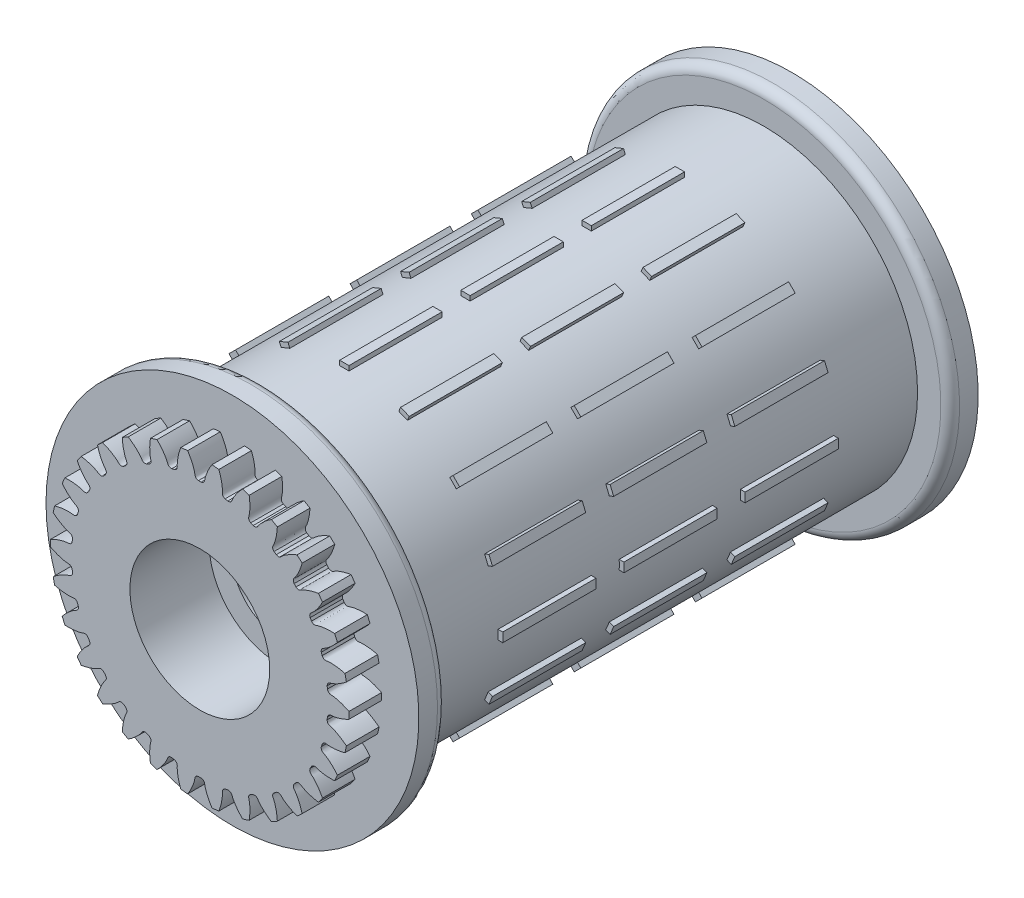
SolidWorks part; units mm, degrees
material "ABS"
ref_plane "前视基准面" through (0, 0, 0) normal (0, 0, 1) x (1, 0, 0)
ref_plane "上视基准面" through (0, 0, 0) normal (0, 1, 0) x (1, 0, 0)
ref_plane "右视基准面" through (0, 0, 0) normal (1, 0, 0) x (0, 0, -1)
other "Configuration Table"
sketch "草图1" plane through (0, 0, 0) normal (0, 1, 0) x (1, 0, 0)
  line L0 (0, 0) -> (0, -60) construction
  line L1 (0, -60) -> (20, -60)
  line L2 (20, -60) -> (20, -57)
  line L3 (20, -57) -> (16.5, -57)
  line L4 (16.5, -57) -> (16.5, -3)
  line L5 (16.5, -3) -> (20, -3)
  line L6 (20, -3) -> (20, 0)
  line L7 (20, 0) -> (0, 0)
  line L8 (7.5, 0) -> (7.5, -5)
  line L9 (7.5, -5) -> (5, -5)
  line L10 (5, -5) -> (5, -55)
  line L11 (5, -55) -> (7.5, -55)
  line L12 (7.5, -55) -> (7.5, -60)
  dimension "D1" = 60
  dimension "D2" = 3
  dimension "D3" = 3
  dimension "D4" = 20
  dimension "D5" = 16.5
  dimension "D6" = 15
  dimension "D7" = 10
  dimension "D8" = 5
  dimension "D9" = 5
  dimension "D10" = 15
revolve "旋转1" add sketch "草图1" angle 360 about L0
fillet "圆角2" radius 1 2 edges at (-20, 0, 57) (-20, 0, 3)
sketch "草图2" plane through (0, 0, 60) normal (0, 0, 1) x (1, 0, 0)
  arc A0 (-2.7162, 13.479) -> (-3.001, 13.4185) centre (0, 0) ccw
  arc A1 (-4.5927, 15.3267) -> (-5.2932, 15.0991) centre (0, 0) ccw
  arc A2 (-5.4593, 12.6198) -> (-5.7253, 12.5013) centre (0, 0) ccw
  arc A3 (-7.6789, 14.0369) -> (-8.3168, 13.6686) centre (0, 0) ccw
  arc A4 (-7.9638, 11.2089) -> (-8.1994, 11.0378) centre (0, 0) ccw
  arc A5 (-10.4296, 12.1336) -> (-10.9769, 11.6407) centre (0, 0) ccw
  arc A6 (-10.1203, 9.3082) -> (-10.3151, 9.0919) centre (0, 0) ccw
  arc A7 (-12.7244, 9.7) -> (-13.1573, 9.1041) centre (0, 0) ccw
  arc A8 (-11.8344, 7.0007) -> (-11.98, 6.7486) centre (0, 0) ccw
  arc A9 (-14.4631, 6.8425) -> (-14.7626, 6.1696) centre (0, 0) ccw
  arc A10 (-13.0313, 4.3872) -> (-13.1213, 4.1103) centre (0, 0) ccw
  arc A11 (-15.5696, 3.6859) -> (-15.7228, 2.9655) centre (0, 0) ccw
  arc A12 (-13.6587, 1.5819) -> (-13.6891, 1.2924) centre (0, 0) ccw
  arc A13 (-15.9958, 0.3683) -> (-15.9958, -0.3683) centre (0, 0) ccw
  arc A14 (-13.6891, -1.2924) -> (-13.6587, -1.5819) centre (0, 0) ccw
  arc A15 (-15.7228, -2.9655) -> (-15.5696, -3.6859) centre (0, 0) ccw
  arc A16 (-13.1213, -4.1103) -> (-13.0313, -4.3872) centre (0, 0) ccw
  arc A17 (-14.7626, -6.1696) -> (-14.4631, -6.8425) centre (0, 0) ccw
  arc A18 (-11.98, -6.7486) -> (-11.8344, -7.0007) centre (0, 0) ccw
  arc A19 (-13.1573, -9.1041) -> (-12.7244, -9.7) centre (0, 0) ccw
  arc A20 (-10.3151, -9.0919) -> (-10.1203, -9.3082) centre (0, 0) ccw
  arc A21 (-10.9769, -11.6407) -> (-10.4296, -12.1336) centre (0, 0) ccw
  arc A22 (-8.1994, -11.0378) -> (-7.9638, -11.2089) centre (0, 0) ccw
  arc A23 (-8.3168, -13.6686) -> (-7.6789, -14.0369) centre (0, 0) ccw
  arc A24 (-5.7253, -12.5013) -> (-5.4593, -12.6198) centre (0, 0) ccw
  arc A25 (-5.2932, -15.0991) -> (-4.5927, -15.3267) centre (0, 0) ccw
  arc A26 (-3.001, -13.4185) -> (-2.7162, -13.479) centre (0, 0) ccw
  arc A27 (-2.0383, -15.8696) -> (-1.3057, -15.9466) centre (0, 0) ccw
  arc A28 (-0.1456, -13.7492) -> (0.1456, -13.7492) centre (0, 0) ccw
  arc A29 (1.3057, -15.9466) -> (2.0383, -15.8696) centre (0, 0) ccw
  arc A30 (2.7162, -13.479) -> (3.001, -13.4185) centre (0, 0) ccw
  arc A31 (4.5927, -15.3267) -> (5.2932, -15.0991) centre (0, 0) ccw
  arc A32 (5.4593, -12.6198) -> (5.7253, -12.5013) centre (0, 0) ccw
  arc A33 (7.6789, -14.0369) -> (8.3168, -13.6686) centre (0, 0) ccw
  arc A34 (7.9638, -11.2089) -> (8.1994, -11.0378) centre (0, 0) ccw
  arc A35 (10.4296, -12.1336) -> (10.9769, -11.6407) centre (0, 0) ccw
  arc A36 (10.1203, -9.3082) -> (10.3151, -9.0919) centre (0, 0) ccw
  arc A37 (12.7244, -9.7) -> (13.1573, -9.1041) centre (0, 0) ccw
  arc A38 (11.8344, -7.0007) -> (11.98, -6.7486) centre (0, 0) ccw
  arc A39 (14.4631, -6.8425) -> (14.7626, -6.1696) centre (0, 0) ccw
  arc A40 (13.0313, -4.3872) -> (13.1213, -4.1103) centre (0, 0) ccw
  arc A41 (15.5696, -3.6859) -> (15.7228, -2.9655) centre (0, 0) ccw
  arc A42 (13.6587, -1.5819) -> (13.6891, -1.2924) centre (0, 0) ccw
  arc A43 (15.9958, -0.3683) -> (15.9958, 0.3683) centre (0, 0) ccw
  arc A44 (13.6891, 1.2924) -> (13.6587, 1.5819) centre (0, 0) ccw
  arc A45 (15.7228, 2.9655) -> (15.5696, 3.6859) centre (0, 0) ccw
  arc A46 (13.1213, 4.1103) -> (13.0313, 4.3872) centre (0, 0) ccw
  arc A47 (14.7626, 6.1696) -> (14.4631, 6.8425) centre (0, 0) ccw
  arc A48 (11.98, 6.7486) -> (11.8344, 7.0007) centre (0, 0) ccw
  arc A49 (13.1573, 9.1041) -> (12.7244, 9.7) centre (0, 0) ccw
  arc A50 (10.3151, 9.0919) -> (10.1203, 9.3082) centre (0, 0) ccw
  arc A51 (10.9769, 11.6407) -> (10.4296, 12.1336) centre (0, 0) ccw
  arc A52 (8.1994, 11.0378) -> (7.9638, 11.2089) centre (0, 0) ccw
  arc A53 (8.3168, 13.6686) -> (7.6789, 14.0369) centre (0, 0) ccw
  arc A54 (5.7253, 12.5013) -> (5.4593, 12.6198) centre (0, 0) ccw
  arc A55 (5.2932, 15.0991) -> (4.5927, 15.3267) centre (0, 0) ccw
  arc A56 (3.001, 13.4185) -> (2.7162, 13.479) centre (0, 0) ccw
  arc A57 (2.0383, 15.8696) -> (1.3057, 15.9466) centre (0, 0) ccw
  arc A58 (0.1456, 13.7492) -> (-0.1456, 13.7492) centre (0, 0) ccw
  arc A59 (-1.3057, 15.9466) -> (-2.0383, 15.8696) centre (0, 0) ccw
  circle A60 centre (0, 0) radius 7.5
  spline S0 degree 3 poles (-3.001, 13.4185) (-3.369, 13.4055) (-3.4197, 13.6341) (-3.5175, 13.8601) (-3.5386, 13.9063) (-3.5727, 13.9775) (-3.6247, 14.0776) (-3.7001, 14.2098) (-3.7927, 14.3581) (-3.9038, 14.5213) (-4.0348, 14.6979) (-4.1869, 14.8868) (-4.3612, 15.0865) (-4.5001, 15.2333) (-4.5801, 15.314) (-4.5927, 15.3267) knots 0.548501 0.548501 0.548501 0.548501 0.663825 0.671913 0.681013 0.691124 0.714378 0.741677 0.77302 0.808408 0.847839 0.891315 0.938834 0.990398 1 1 1 1
  spline S1 degree 3 poles (-5.2932, 15.0991) (-5.3109, 14.9867) (-5.3377, 14.7864) (-5.363, 14.5047) (-5.375, 14.2625) (-5.3771, 14.0426) (-5.372, 13.8735) (-5.3628, 13.7234) (-5.353, 13.6148) (-5.3383, 13.4935) (-5.3254, 13.408) (-5.3112, 13.3304) (-5.301, 13.2806) (-5.2473, 13.0403) (-5.154, 12.8255) (-5.4593, 12.6198) knots 0 0 0 0 0.061166 0.108685 0.152161 0.191592 0.22698 0.243157 0.272478 0.285622 0.308876 0.318987 0.328087 0.336175 0.451499 0.451499 0.451499 0.451499
  spline S2 degree 3 poles (-5.7253, 12.5013) (-6.0825, 12.4121) (-6.1797, 12.6251) (-6.3223, 12.8259) (-6.3525, 12.8667) (-6.4007, 12.9292) (-6.4724, 13.0163) (-6.5736, 13.13) (-6.6951, 13.2558) (-6.8377, 13.3923) (-7.0025, 13.5379) (-7.1905, 13.691) (-7.4026, 13.85) (-7.5689, 13.9647) (-7.664, 14.0271) (-7.6789, 14.0369) knots 0.548501 0.548501 0.548501 0.548501 0.663825 0.671913 0.681013 0.691124 0.714378 0.741677 0.77302 0.808408 0.847839 0.891315 0.938834 0.990398 1 1 1 1
  spline S3 degree 3 poles (-8.3168, 13.6686) (-8.3107, 13.5551) (-8.2953, 13.3536) (-8.2615, 13.0727) (-8.2229, 12.8333) (-8.1792, 12.6177) (-8.139, 12.4534) (-8.0989, 12.3085) (-8.0667, 12.2043) (-8.0271, 12.0888) (-7.9967, 12.0078) (-7.9666, 11.9348) (-7.9464, 11.8883) (-7.8439, 11.6643) (-7.7079, 11.4737) (-7.9638, 11.2089) knots 0 0 0 0 0.061166 0.108685 0.152161 0.191592 0.22698 0.243157 0.272478 0.285622 0.308876 0.318987 0.328087 0.336175 0.451499 0.451499 0.451499 0.451499
  spline S4 degree 3 poles (-8.1994, 11.0378) (-8.5302, 10.8762) (-8.6695, 11.0644) (-8.8508, 11.2311) (-8.8888, 11.2648) (-8.949, 11.3159) (-9.0372, 11.3862) (-9.1599, 11.4764) (-9.3048, 11.5742) (-9.4727, 11.678) (-9.6642, 11.7861) (-9.8799, 11.8968) (-10.1204, 12.0083) (-10.307, 12.0859) (-10.4129, 12.1272) (-10.4296, 12.1336) knots 0.548501 0.548501 0.548501 0.548501 0.663825 0.671913 0.681013 0.691124 0.714378 0.741677 0.77302 0.808408 0.847839 0.891315 0.938834 0.990398 1 1 1 1
  spline S5 degree 3 poles (-10.9769, 11.6407) (-10.9474, 11.531) (-10.8904, 11.3371) (-10.7989, 11.0694) (-10.7114, 10.8432) (-10.6239, 10.6414) (-10.5504, 10.489) (-10.481, 10.3557) (-10.4278, 10.2605) (-10.365, 10.1557) (-10.3185, 10.0828) (-10.2739, 10.0176) (-10.2444, 9.9763) (-10.0976, 9.7786) (-9.925, 9.6204) (-10.1203, 9.3082) knots 0 0 0 0 0.061166 0.108685 0.152161 0.191592 0.22698 0.243157 0.272478 0.285622 0.308876 0.318987 0.328087 0.336175 0.451499 0.451499 0.451499 0.451499
  spline S6 degree 3 poles (-10.3151, 9.0919) (-10.6051, 8.865) (-10.7805, 9.0201) (-10.9925, 9.1455) (-11.0367, 9.1705) (-11.1061, 9.208) (-11.207, 9.2585) (-11.3458, 9.3211) (-11.5079, 9.3867) (-11.6936, 9.4533) (-11.9035, 9.5193) (-12.1375, 9.5827) (-12.3959, 9.6417) (-12.5945, 9.6789) (-12.7067, 9.6972) (-12.7244, 9.7) knots 0.548501 0.548501 0.548501 0.548501 0.663825 0.671913 0.681013 0.691124 0.714378 0.741677 0.77302 0.808408 0.847839 0.891315 0.938834 0.990398 1 1 1 1
  spline S7 degree 3 poles (-13.1573, 9.1041) (-13.1056, 9.0029) (-13.0096, 8.8251) (-12.8644, 8.5823) (-12.7317, 8.3793) (-12.6042, 8.2001) (-12.5006, 8.0663) (-12.405, 7.9503) (-12.3332, 7.8682) (-12.25, 7.7787) (-12.1893, 7.7171) (-12.1322, 7.6627) (-12.0948, 7.6284) (-11.91, 7.4655) (-11.7083, 7.3466) (-11.8344, 7.0007) knots 0 0 0 0 0.061166 0.108685 0.152161 0.191592 0.22698 0.243157 0.272478 0.285622 0.308876 0.318987 0.328087 0.336175 0.451499 0.451499 0.451499 0.451499
  spline S8 degree 3 poles (-11.98, 6.7486) (-12.2165, 6.4663) (-12.4203, 6.5816) (-12.6538, 6.6602) (-12.7022, 6.6755) (-12.7779, 6.6977) (-12.8871, 6.7261) (-13.0358, 6.7585) (-13.208, 6.7889) (-13.4036, 6.8155) (-13.6225, 6.8364) (-13.8646, 6.8498) (-14.1297, 6.8538) (-14.3317, 6.8488) (-14.4452, 6.8434) (-14.4631, 6.8425) knots 0.548501 0.548501 0.548501 0.548501 0.663825 0.671913 0.681013 0.691124 0.714378 0.741677 0.77302 0.808408 0.847839 0.891315 0.938834 0.990398 1 1 1 1
  spline S9 degree 3 poles (-14.7626, 6.1696) (-14.691, 6.0814) (-14.5601, 5.9274) (-14.3676, 5.7201) (-14.1957, 5.5491) (-14.0336, 5.4003) (-13.9045, 5.291) (-13.7869, 5.1974) (-13.6996, 5.132) (-13.5996, 5.0618) (-13.5275, 5.0142) (-13.4602, 4.9728) (-13.4165, 4.947) (-13.2019, 4.8261) (-12.9799, 4.7518) (-13.0313, 4.3872) knots 0 0 0 0 0.061166 0.108685 0.152161 0.191592 0.22698 0.243157 0.272478 0.285622 0.308876 0.318987 0.328087 0.336175 0.451499 0.451499 0.451499 0.451499
  spline S10 degree 3 poles (-13.1213, 4.1103) (-13.294, 3.7851) (-13.5173, 3.8555) (-13.762, 3.8838) (-13.8125, 3.8887) (-13.8912, 3.8947) (-14.0039, 3.8997) (-14.1561, 3.9005) (-14.3309, 3.8945) (-14.5277, 3.8798) (-14.7462, 3.8547) (-14.9858, 3.8174) (-15.2459, 3.7663) (-15.4424, 3.7194) (-15.5524, 3.6905) (-15.5696, 3.6859) knots 0.548501 0.548501 0.548501 0.548501 0.663825 0.671913 0.681013 0.691124 0.714378 0.741677 0.77302 0.808408 0.847839 0.891315 0.938834 0.990398 1 1 1 1
  spline S11 degree 3 poles (-15.7228, 2.9655) (-15.6343, 2.894) (-15.4743, 2.7706) (-15.2429, 2.6079) (-15.0392, 2.4764) (-14.8498, 2.3646) (-14.7008, 2.2845) (-14.5662, 2.2174) (-14.4673, 2.1716) (-14.3549, 2.1237) (-14.2744, 2.0921) (-14.2, 2.0656) (-14.1519, 2.0495) (-13.9168, 1.9758) (-13.6842, 1.9493) (-13.6587, 1.5819) knots 0 0 0 0 0.061166 0.108685 0.152161 0.191592 0.22698 0.243157 0.272478 0.285622 0.308876 0.318987 0.328087 0.336175 0.451499 0.451499 0.451499 0.451499
  spline S12 degree 3 poles (-13.6891, 1.2924) (-13.7904, 0.9384) (-14.0235, 0.9608) (-14.2687, 0.9376) (-14.3192, 0.9319) (-14.3974, 0.9214) (-14.5087, 0.903) (-14.6578, 0.8721) (-14.8274, 0.8298) (-15.0169, 0.7745) (-15.2254, 0.7046) (-15.452, 0.6183) (-15.6958, 0.5142) (-15.8783, 0.4275) (-15.9798, 0.3764) (-15.9958, 0.3683) knots 0.548501 0.548501 0.548501 0.548501 0.663825 0.671913 0.681013 0.691124 0.714378 0.741677 0.77302 0.808408 0.847839 0.891315 0.938834 0.990398 1 1 1 1
  spline S13 degree 3 poles (-15.9958, -0.3683) (-15.8944, -0.4198) (-15.7122, -0.5072) (-15.452, -0.6183) (-15.2254, -0.7046) (-15.0169, -0.7745) (-14.8545, -0.8219) (-14.7089, -0.8596) (-14.6026, -0.8838) (-14.4827, -0.9073) (-14.3974, -0.9214) (-14.3192, -0.9319) (-14.2687, -0.9376) (-14.0235, -0.9608) (-13.7904, -0.9384) (-13.6891, -1.2924) knots 0 0 0 0 0.061166 0.108685 0.152161 0.191592 0.22698 0.243157 0.272478 0.285622 0.308876 0.318987 0.328087 0.336175 0.451499 0.451499 0.451499 0.451499
  spline S14 degree 3 poles (-13.6587, -1.5819) (-13.6842, -1.9493) (-13.9168, -1.9758) (-14.1519, -2.0495) (-14.2, -2.0656) (-14.2744, -2.0921) (-14.3794, -2.1333) (-14.5188, -2.1945) (-14.6759, -2.2711) (-14.8498, -2.3646) (-15.0392, -2.4764) (-15.2429, -2.6079) (-15.4597, -2.7604) (-15.6202, -2.8831) (-15.7089, -2.9543) (-15.7228, -2.9655) knots 0.548501 0.548501 0.548501 0.548501 0.663825 0.671913 0.681013 0.691124 0.714378 0.741677 0.77302 0.808408 0.847839 0.891315 0.938834 0.990398 1 1 1 1
  spline S15 degree 3 poles (-15.5696, -3.6859) (-15.4598, -3.7152) (-15.2634, -3.7629) (-14.9858, -3.8174) (-14.7462, -3.8547) (-14.5277, -3.8798) (-14.359, -3.8924) (-14.2088, -3.8989) (-14.0997, -3.9005) (-13.9776, -3.8986) (-13.8912, -3.8947) (-13.8125, -3.8887) (-13.762, -3.8838) (-13.5173, -3.8555) (-13.294, -3.7851) (-13.1213, -4.1103) knots 0 0 0 0 0.061166 0.108685 0.152161 0.191592 0.22698 0.243157 0.272478 0.285622 0.308876 0.318987 0.328087 0.336175 0.451499 0.451499 0.451499 0.451499
  spline S16 degree 3 poles (-13.0313, -4.3872) (-12.9799, -4.7518) (-13.2019, -4.8261) (-13.4165, -4.947) (-13.4602, -4.9728) (-13.5275, -5.0142) (-13.6216, -5.0763) (-13.7452, -5.1652) (-13.883, -5.2728) (-14.0336, -5.4003) (-14.1957, -5.5491) (-14.3676, -5.7201) (-14.5479, -5.9143) (-14.6794, -6.0678) (-14.7514, -6.1558) (-14.7626, -6.1696) knots 0.548501 0.548501 0.548501 0.548501 0.663825 0.671913 0.681013 0.691124 0.714378 0.741677 0.77302 0.808408 0.847839 0.891315 0.938834 0.990398 1 1 1 1
  spline S17 degree 3 poles (-14.4631, -6.8425) (-14.3495, -6.8483) (-14.1475, -6.8541) (-13.8646, -6.8498) (-13.6225, -6.8364) (-13.4036, -6.8155) (-13.2359, -6.7927) (-13.0876, -6.7679) (-12.9807, -6.7468) (-12.8616, -6.7195) (-12.7779, -6.6977) (-12.7022, -6.6755) (-12.6538, -6.6602) (-12.4203, -6.5816) (-12.2165, -6.4663) (-11.98, -6.7486) knots 0 0 0 0 0.061166 0.108685 0.152161 0.191592 0.22698 0.243157 0.272478 0.285622 0.308876 0.318987 0.328087 0.336175 0.451499 0.451499 0.451499 0.451499
  spline S18 degree 3 poles (-11.8344, -7.0007) (-11.7083, -7.3466) (-11.91, -7.4655) (-12.0948, -7.6284) (-12.1322, -7.6627) (-12.1893, -7.7171) (-12.2685, -7.7975) (-12.371, -7.9101) (-12.4834, -8.044) (-12.6042, -8.2001) (-12.7317, -8.3793) (-12.8644, -8.5823) (-13.0004, -8.8097) (-13.0971, -8.9872) (-13.1492, -9.0882) (-13.1573, -9.1041) knots 0.548501 0.548501 0.548501 0.548501 0.663825 0.671913 0.681013 0.691124 0.714378 0.741677 0.77302 0.808408 0.847839 0.891315 0.938834 0.990398 1 1 1 1
  spline S19 degree 3 poles (-12.7244, -9.7) (-12.6121, -9.6821) (-12.4133, -9.6457) (-12.1375, -9.5827) (-11.9035, -9.5193) (-11.6936, -9.4533) (-11.5344, -9.3962) (-11.3945, -9.3411) (-11.2943, -9.2982) (-11.1835, -9.2467) (-11.1061, -9.208) (-11.0367, -9.1705) (-10.9925, -9.1455) (-10.7805, -9.0201) (-10.6051, -8.865) (-10.3151, -9.0919) knots 0 0 0 0 0.061166 0.108685 0.152161 0.191592 0.22698 0.243157 0.272478 0.285622 0.308876 0.318987 0.328087 0.336175 0.451499 0.451499 0.451499 0.451499
  spline S20 degree 3 poles (-10.1203, -9.3082) (-9.925, -9.6204) (-10.0976, -9.7786) (-10.2444, -9.9763) (-10.2739, -10.0176) (-10.3185, -10.0828) (-10.3792, -10.1778) (-10.456, -10.3093) (-10.5382, -10.4636) (-10.6239, -10.6415) (-10.7114, -10.8432) (-10.7989, -11.0694) (-10.8847, -11.3202) (-10.9423, -11.5138) (-10.9723, -11.6235) (-10.9769, -11.6407) knots 0.548501 0.548501 0.548501 0.548501 0.663825 0.671913 0.681013 0.691124 0.714378 0.741677 0.77302 0.808408 0.847839 0.891315 0.938834 0.990398 1 1 1 1
  spline S21 degree 3 poles (-10.4296, -12.1336) (-10.3235, -12.0927) (-10.1366, -12.0158) (-9.8799, -11.8968) (-9.6642, -11.7861) (-9.4727, -11.678) (-9.3288, -11.589) (-9.2034, -11.506) (-9.1142, -11.4432) (-9.0166, -11.3698) (-8.949, -11.3159) (-8.8888, -11.2648) (-8.8508, -11.2311) (-8.6695, -11.0644) (-8.5302, -10.8762) (-8.1994, -11.0378) knots 0 0 0 0 0.061166 0.108685 0.152161 0.191592 0.22698 0.243157 0.272478 0.285622 0.308876 0.318987 0.328087 0.336175 0.451499 0.451499 0.451499 0.451499
  spline S22 degree 3 poles (-7.9638, -11.2089) (-7.7079, -11.4737) (-7.8439, -11.6643) (-7.9464, -11.8883) (-7.9666, -11.9348) (-7.9967, -12.0078) (-8.0363, -12.1134) (-8.0841, -12.258) (-8.1324, -12.426) (-8.1792, -12.6177) (-8.2229, -12.8333) (-8.2615, -13.0727) (-8.2932, -13.3358) (-8.3094, -13.5373) (-8.3159, -13.6508) (-8.3168, -13.6686) knots 0.548501 0.548501 0.548501 0.548501 0.663825 0.671913 0.681013 0.691124 0.714378 0.741677 0.77302 0.808408 0.847839 0.891315 0.938834 0.990398 1 1 1 1
  spline S23 degree 3 poles (-7.6789, -14.0369) (-7.5837, -13.9748) (-7.4169, -13.8608) (-7.1905, -13.691) (-7.0025, -13.5379) (-6.8377, -13.3923) (-6.7154, -13.2753) (-6.61, -13.1681) (-6.5359, -13.0881) (-6.4556, -12.996) (-6.4007, -12.9292) (-6.3525, -12.8667) (-6.3223, -12.8259) (-6.1797, -12.6251) (-6.0825, -12.4121) (-5.7253, -12.5013) knots 0 0 0 0 0.061166 0.108685 0.152161 0.191592 0.22698 0.243157 0.272478 0.285622 0.308876 0.318987 0.328087 0.336175 0.451499 0.451499 0.451499 0.451499
  spline S24 degree 3 poles (-5.4593, -12.6198) (-5.154, -12.8255) (-5.2473, -13.0403) (-5.301, -13.2806) (-5.3112, -13.3304) (-5.3254, -13.408) (-5.3422, -13.5195) (-5.3589, -13.6709) (-5.3711, -13.8453) (-5.3771, -14.0426) (-5.375, -14.2625) (-5.363, -14.5047) (-5.3393, -14.7687) (-5.3132, -14.9691) (-5.296, -15.0814) (-5.2932, -15.0991) knots 0.548501 0.548501 0.548501 0.548501 0.663825 0.671913 0.681013 0.691124 0.714378 0.741677 0.77302 0.808408 0.847839 0.891315 0.938834 0.990398 1 1 1 1
  spline S25 degree 3 poles (-4.5927, -15.3267) (-4.5124, -15.2462) (-4.373, -15.0999) (-4.1869, -14.8868) (-4.0348, -14.6979) (-3.9038, -14.5213) (-3.8086, -14.3814) (-3.7278, -14.2546) (-3.6719, -14.161) (-3.6125, -14.0542) (-3.5727, -13.9775) (-3.5386, -13.9063) (-3.5175, -13.8601) (-3.4197, -13.6341) (-3.369, -13.4055) (-3.001, -13.4185) knots 0 0 0 0 0.061166 0.108685 0.152161 0.191592 0.22698 0.243157 0.272478 0.285622 0.308876 0.318987 0.328087 0.336175 0.451499 0.451499 0.451499 0.451499
  spline S26 degree 3 poles (-2.7162, -13.479) (-2.3748, -13.6168) (-2.4214, -13.8463) (-2.424, -14.0926) (-2.4236, -14.1433) (-2.4213, -14.2222) (-2.4146, -14.3348) (-2.3994, -14.4863) (-2.3752, -14.6594) (-2.34, -14.8537) (-2.2922, -15.0683) (-2.2301, -15.3027) (-2.152, -15.556) (-2.0849, -15.7466) (-2.0447, -15.853) (-2.0383, -15.8696) knots 0.548501 0.548501 0.548501 0.548501 0.663825 0.671913 0.681013 0.691124 0.714378 0.741677 0.77302 0.808408 0.847839 0.891315 0.938834 0.990398 1 1 1 1
  spline S27 degree 3 poles (-1.3057, -15.9466) (-1.2439, -15.8512) (-1.138, -15.6791) (-1.0003, -15.432) (-0.8908, -15.2156) (-0.7994, -15.0156) (-0.7353, -14.859) (-0.6826, -14.7182) (-0.6474, -14.615) (-0.6116, -14.4982) (-0.5886, -14.4148) (-0.57, -14.3381) (-0.559, -14.2886) (-0.5103, -14.0471) (-0.5082, -13.813) (-0.1456, -13.7492) knots 0 0 0 0 0.061166 0.108685 0.152161 0.191592 0.22698 0.243157 0.272478 0.285622 0.308876 0.318987 0.328087 0.336175 0.451499 0.451499 0.451499 0.451499
  spline S28 degree 3 poles (0.1456, -13.7492) (0.5082, -13.813) (0.5103, -14.0471) (0.559, -14.2886) (0.57, -14.3381) (0.5886, -14.4148) (0.6186, -14.5236) (0.6649, -14.6686) (0.7246, -14.8329) (0.7994, -15.0156) (0.8908, -15.2156) (1.0003, -15.432) (1.1293, -15.6635) (1.2346, -15.836) (1.296, -15.9316) (1.3057, -15.9466) knots 0.548501 0.548501 0.548501 0.548501 0.663825 0.671913 0.681013 0.691124 0.714378 0.741677 0.77302 0.808408 0.847839 0.891315 0.938834 0.990398 1 1 1 1
  spline S29 degree 3 poles (2.0383, -15.8696) (2.0789, -15.7634) (2.1468, -15.5731) (2.2301, -15.3027) (2.2922, -15.0683) (2.34, -14.8537) (2.3701, -14.6872) (2.3924, -14.5385) (2.4054, -14.4302) (2.4161, -14.3085) (2.4213, -14.2222) (2.4236, -14.1433) (2.424, -14.0926) (2.4214, -13.8463) (2.3748, -13.6168) (2.7162, -13.479) knots 0 0 0 0 0.061166 0.108685 0.152161 0.191592 0.22698 0.243157 0.272478 0.285622 0.308876 0.318987 0.328087 0.336175 0.451499 0.451499 0.451499 0.451499
  spline S30 degree 3 poles (3.001, -13.4185) (3.369, -13.4055) (3.4197, -13.6341) (3.5175, -13.8601) (3.5386, -13.9063) (3.5727, -13.9775) (3.6247, -14.0776) (3.7001, -14.2098) (3.7927, -14.3581) (3.9038, -14.5213) (4.0348, -14.6979) (4.1869, -14.8868) (4.3612, -15.0865) (4.5001, -15.2333) (4.5801, -15.314) (4.5927, -15.3267) knots 0.548501 0.548501 0.548501 0.548501 0.663825 0.671913 0.681013 0.691124 0.714378 0.741677 0.77302 0.808408 0.847839 0.891315 0.938834 0.990398 1 1 1 1
  spline S31 degree 3 poles (5.2932, -15.0991) (5.3109, -14.9867) (5.3377, -14.7864) (5.363, -14.5047) (5.375, -14.2625) (5.3771, -14.0426) (5.372, -13.8735) (5.3628, -13.7234) (5.353, -13.6148) (5.3383, -13.4935) (5.3254, -13.408) (5.3112, -13.3304) (5.301, -13.2806) (5.2473, -13.0403) (5.154, -12.8255) (5.4593, -12.6198) knots 0 0 0 0 0.061166 0.108685 0.152161 0.191592 0.22698 0.243157 0.272478 0.285622 0.308876 0.318987 0.328087 0.336175 0.451499 0.451499 0.451499 0.451499
  spline S32 degree 3 poles (5.7253, -12.5013) (6.0825, -12.4121) (6.1797, -12.6251) (6.3223, -12.8259) (6.3525, -12.8667) (6.4007, -12.9292) (6.4724, -13.0163) (6.5736, -13.13) (6.6951, -13.2558) (6.8377, -13.3923) (7.0025, -13.5379) (7.1905, -13.691) (7.4026, -13.85) (7.5689, -13.9647) (7.664, -14.0271) (7.6789, -14.0369) knots 0.548501 0.548501 0.548501 0.548501 0.663825 0.671913 0.681013 0.691124 0.714378 0.741677 0.77302 0.808408 0.847839 0.891315 0.938834 0.990398 1 1 1 1
  spline S33 degree 3 poles (8.3168, -13.6686) (8.3107, -13.5551) (8.2953, -13.3536) (8.2615, -13.0727) (8.2229, -12.8333) (8.1792, -12.6177) (8.139, -12.4534) (8.0989, -12.3085) (8.0667, -12.2043) (8.0271, -12.0888) (7.9967, -12.0078) (7.9666, -11.9348) (7.9464, -11.8883) (7.8439, -11.6643) (7.7079, -11.4737) (7.9638, -11.2089) knots 0 0 0 0 0.061166 0.108685 0.152161 0.191592 0.22698 0.243157 0.272478 0.285622 0.308876 0.318987 0.328087 0.336175 0.451499 0.451499 0.451499 0.451499
  spline S34 degree 3 poles (8.1994, -11.0378) (8.5302, -10.8762) (8.6695, -11.0644) (8.8508, -11.2311) (8.8888, -11.2648) (8.949, -11.3159) (9.0372, -11.3862) (9.1599, -11.4764) (9.3048, -11.5742) (9.4727, -11.678) (9.6642, -11.7861) (9.8799, -11.8968) (10.1204, -12.0083) (10.307, -12.0859) (10.4129, -12.1272) (10.4296, -12.1336) knots 0.548501 0.548501 0.548501 0.548501 0.663825 0.671913 0.681013 0.691124 0.714378 0.741677 0.77302 0.808408 0.847839 0.891315 0.938834 0.990398 1 1 1 1
  spline S35 degree 3 poles (10.9769, -11.6407) (10.9474, -11.531) (10.8904, -11.3371) (10.7989, -11.0694) (10.7114, -10.8432) (10.6239, -10.6414) (10.5504, -10.489) (10.481, -10.3557) (10.4278, -10.2605) (10.365, -10.1557) (10.3185, -10.0828) (10.2739, -10.0176) (10.2444, -9.9763) (10.0976, -9.7786) (9.925, -9.6204) (10.1203, -9.3082) knots 0 0 0 0 0.061166 0.108685 0.152161 0.191592 0.22698 0.243157 0.272478 0.285622 0.308876 0.318987 0.328087 0.336175 0.451499 0.451499 0.451499 0.451499
  spline S36 degree 3 poles (10.3151, -9.0919) (10.6051, -8.865) (10.7805, -9.0201) (10.9925, -9.1455) (11.0367, -9.1705) (11.1061, -9.208) (11.207, -9.2585) (11.3458, -9.3211) (11.5079, -9.3867) (11.6936, -9.4533) (11.9035, -9.5193) (12.1375, -9.5827) (12.3959, -9.6417) (12.5945, -9.6789) (12.7067, -9.6972) (12.7244, -9.7) knots 0.548501 0.548501 0.548501 0.548501 0.663825 0.671913 0.681013 0.691124 0.714378 0.741677 0.77302 0.808408 0.847839 0.891315 0.938834 0.990398 1 1 1 1
  spline S37 degree 3 poles (13.1573, -9.1041) (13.1056, -9.0029) (13.0096, -8.8251) (12.8644, -8.5823) (12.7317, -8.3793) (12.6042, -8.2001) (12.5006, -8.0663) (12.405, -7.9503) (12.3332, -7.8682) (12.25, -7.7787) (12.1893, -7.7171) (12.1322, -7.6627) (12.0948, -7.6284) (11.91, -7.4655) (11.7083, -7.3466) (11.8344, -7.0007) knots 0 0 0 0 0.061166 0.108685 0.152161 0.191592 0.22698 0.243157 0.272478 0.285622 0.308876 0.318987 0.328087 0.336175 0.451499 0.451499 0.451499 0.451499
  spline S38 degree 3 poles (11.98, -6.7486) (12.2165, -6.4663) (12.4203, -6.5816) (12.6538, -6.6602) (12.7022, -6.6755) (12.7779, -6.6977) (12.8871, -6.7261) (13.0358, -6.7585) (13.208, -6.7889) (13.4036, -6.8155) (13.6225, -6.8364) (13.8646, -6.8498) (14.1297, -6.8538) (14.3317, -6.8488) (14.4452, -6.8434) (14.4631, -6.8425) knots 0.548501 0.548501 0.548501 0.548501 0.663825 0.671913 0.681013 0.691124 0.714378 0.741677 0.77302 0.808408 0.847839 0.891315 0.938834 0.990398 1 1 1 1
  spline S39 degree 3 poles (14.7626, -6.1696) (14.691, -6.0814) (14.5601, -5.9274) (14.3676, -5.7201) (14.1957, -5.5491) (14.0336, -5.4003) (13.9045, -5.291) (13.7869, -5.1974) (13.6996, -5.132) (13.5996, -5.0618) (13.5275, -5.0142) (13.4602, -4.9728) (13.4165, -4.947) (13.2019, -4.8261) (12.9799, -4.7518) (13.0313, -4.3872) knots 0 0 0 0 0.061166 0.108685 0.152161 0.191592 0.22698 0.243157 0.272478 0.285622 0.308876 0.318987 0.328087 0.336175 0.451499 0.451499 0.451499 0.451499
  spline S40 degree 3 poles (13.1213, -4.1103) (13.294, -3.7851) (13.5173, -3.8555) (13.762, -3.8838) (13.8125, -3.8887) (13.8912, -3.8947) (14.0039, -3.8997) (14.1561, -3.9005) (14.3309, -3.8945) (14.5277, -3.8798) (14.7462, -3.8547) (14.9858, -3.8174) (15.2459, -3.7663) (15.4424, -3.7194) (15.5524, -3.6905) (15.5696, -3.6859) knots 0.548501 0.548501 0.548501 0.548501 0.663825 0.671913 0.681013 0.691124 0.714378 0.741677 0.77302 0.808408 0.847839 0.891315 0.938834 0.990398 1 1 1 1
  spline S41 degree 3 poles (15.7228, -2.9655) (15.6343, -2.894) (15.4743, -2.7706) (15.2429, -2.6079) (15.0392, -2.4764) (14.8498, -2.3646) (14.7008, -2.2845) (14.5662, -2.2174) (14.4673, -2.1716) (14.3549, -2.1237) (14.2744, -2.0921) (14.2, -2.0656) (14.1519, -2.0495) (13.9168, -1.9758) (13.6842, -1.9493) (13.6587, -1.5819) knots 0 0 0 0 0.061166 0.108685 0.152161 0.191592 0.22698 0.243157 0.272478 0.285622 0.308876 0.318987 0.328087 0.336175 0.451499 0.451499 0.451499 0.451499
  spline S42 degree 3 poles (13.6891, -1.2924) (13.7904, -0.9384) (14.0235, -0.9608) (14.2687, -0.9376) (14.3192, -0.9319) (14.3974, -0.9214) (14.5087, -0.903) (14.6578, -0.8721) (14.8274, -0.8298) (15.0169, -0.7745) (15.2254, -0.7046) (15.452, -0.6183) (15.6958, -0.5142) (15.8783, -0.4275) (15.9798, -0.3764) (15.9958, -0.3683) knots 0.548501 0.548501 0.548501 0.548501 0.663825 0.671913 0.681013 0.691124 0.714378 0.741677 0.77302 0.808408 0.847839 0.891315 0.938834 0.990398 1 1 1 1
  spline S43 degree 3 poles (15.9958, 0.3683) (15.8944, 0.4198) (15.7122, 0.5072) (15.452, 0.6183) (15.2254, 0.7046) (15.0169, 0.7745) (14.8545, 0.8219) (14.7089, 0.8596) (14.6026, 0.8838) (14.4827, 0.9073) (14.3974, 0.9214) (14.3192, 0.9319) (14.2687, 0.9376) (14.0235, 0.9608) (13.7904, 0.9384) (13.6891, 1.2924) knots 0 0 0 0 0.061166 0.108685 0.152161 0.191592 0.22698 0.243157 0.272478 0.285622 0.308876 0.318987 0.328087 0.336175 0.451499 0.451499 0.451499 0.451499
  spline S44 degree 3 poles (13.6587, 1.5819) (13.6842, 1.9493) (13.9168, 1.9758) (14.1519, 2.0495) (14.2, 2.0656) (14.2744, 2.0921) (14.3794, 2.1333) (14.5188, 2.1945) (14.6759, 2.2711) (14.8498, 2.3646) (15.0392, 2.4764) (15.2429, 2.6079) (15.4597, 2.7604) (15.6202, 2.8831) (15.7089, 2.9543) (15.7228, 2.9655) knots 0.548501 0.548501 0.548501 0.548501 0.663825 0.671913 0.681013 0.691124 0.714378 0.741677 0.77302 0.808408 0.847839 0.891315 0.938834 0.990398 1 1 1 1
  spline S45 degree 3 poles (15.5696, 3.6859) (15.4598, 3.7152) (15.2634, 3.7629) (14.9858, 3.8174) (14.7462, 3.8547) (14.5277, 3.8798) (14.359, 3.8924) (14.2088, 3.8989) (14.0997, 3.9005) (13.9776, 3.8986) (13.8912, 3.8947) (13.8125, 3.8887) (13.762, 3.8838) (13.5173, 3.8555) (13.294, 3.7851) (13.1213, 4.1103) knots 0 0 0 0 0.061166 0.108685 0.152161 0.191592 0.22698 0.243157 0.272478 0.285622 0.308876 0.318987 0.328087 0.336175 0.451499 0.451499 0.451499 0.451499
  spline S46 degree 3 poles (13.0313, 4.3872) (12.9799, 4.7518) (13.2019, 4.8261) (13.4165, 4.947) (13.4602, 4.9728) (13.5275, 5.0142) (13.6216, 5.0763) (13.7452, 5.1652) (13.883, 5.2728) (14.0336, 5.4003) (14.1957, 5.5491) (14.3676, 5.7201) (14.5479, 5.9143) (14.6794, 6.0678) (14.7514, 6.1558) (14.7626, 6.1696) knots 0.548501 0.548501 0.548501 0.548501 0.663825 0.671913 0.681013 0.691124 0.714378 0.741677 0.77302 0.808408 0.847839 0.891315 0.938834 0.990398 1 1 1 1
  spline S47 degree 3 poles (14.4631, 6.8425) (14.3495, 6.8483) (14.1475, 6.8541) (13.8646, 6.8498) (13.6225, 6.8364) (13.4036, 6.8155) (13.2359, 6.7927) (13.0876, 6.7679) (12.9807, 6.7468) (12.8616, 6.7195) (12.7779, 6.6977) (12.7022, 6.6755) (12.6538, 6.6602) (12.4203, 6.5816) (12.2165, 6.4663) (11.98, 6.7486) knots 0 0 0 0 0.061166 0.108685 0.152161 0.191592 0.22698 0.243157 0.272478 0.285622 0.308876 0.318987 0.328087 0.336175 0.451499 0.451499 0.451499 0.451499
  spline S48 degree 3 poles (11.8344, 7.0007) (11.7083, 7.3466) (11.91, 7.4655) (12.0948, 7.6284) (12.1322, 7.6627) (12.1893, 7.7171) (12.2685, 7.7975) (12.371, 7.9101) (12.4834, 8.044) (12.6042, 8.2001) (12.7317, 8.3793) (12.8644, 8.5823) (13.0004, 8.8097) (13.0971, 8.9872) (13.1492, 9.0882) (13.1573, 9.1041) knots 0.548501 0.548501 0.548501 0.548501 0.663825 0.671913 0.681013 0.691124 0.714378 0.741677 0.77302 0.808408 0.847839 0.891315 0.938834 0.990398 1 1 1 1
  spline S49 degree 3 poles (12.7244, 9.7) (12.6121, 9.6821) (12.4133, 9.6457) (12.1375, 9.5827) (11.9035, 9.5193) (11.6936, 9.4533) (11.5344, 9.3962) (11.3945, 9.3411) (11.2943, 9.2982) (11.1835, 9.2467) (11.1061, 9.208) (11.0367, 9.1705) (10.9925, 9.1455) (10.7805, 9.0201) (10.6051, 8.865) (10.3151, 9.0919) knots 0 0 0 0 0.061166 0.108685 0.152161 0.191592 0.22698 0.243157 0.272478 0.285622 0.308876 0.318987 0.328087 0.336175 0.451499 0.451499 0.451499 0.451499
  spline S50 degree 3 poles (10.1203, 9.3082) (9.925, 9.6204) (10.0976, 9.7786) (10.2444, 9.9763) (10.2739, 10.0176) (10.3185, 10.0828) (10.3792, 10.1778) (10.456, 10.3093) (10.5382, 10.4636) (10.6239, 10.6415) (10.7114, 10.8432) (10.7989, 11.0694) (10.8847, 11.3202) (10.9423, 11.5138) (10.9723, 11.6235) (10.9769, 11.6407) knots 0.548501 0.548501 0.548501 0.548501 0.663825 0.671913 0.681013 0.691124 0.714378 0.741677 0.77302 0.808408 0.847839 0.891315 0.938834 0.990398 1 1 1 1
  spline S51 degree 3 poles (10.4296, 12.1336) (10.3235, 12.0927) (10.1366, 12.0158) (9.8799, 11.8968) (9.6642, 11.7861) (9.4727, 11.678) (9.3288, 11.589) (9.2034, 11.506) (9.1142, 11.4432) (9.0166, 11.3698) (8.949, 11.3159) (8.8888, 11.2648) (8.8508, 11.2311) (8.6695, 11.0644) (8.5302, 10.8762) (8.1994, 11.0378) knots 0 0 0 0 0.061166 0.108685 0.152161 0.191592 0.22698 0.243157 0.272478 0.285622 0.308876 0.318987 0.328087 0.336175 0.451499 0.451499 0.451499 0.451499
  spline S52 degree 3 poles (7.9638, 11.2089) (7.7079, 11.4737) (7.8439, 11.6643) (7.9464, 11.8883) (7.9666, 11.9348) (7.9967, 12.0078) (8.0363, 12.1134) (8.0841, 12.258) (8.1324, 12.426) (8.1792, 12.6177) (8.2229, 12.8333) (8.2615, 13.0727) (8.2932, 13.3358) (8.3094, 13.5373) (8.3159, 13.6508) (8.3168, 13.6686) knots 0.548501 0.548501 0.548501 0.548501 0.663825 0.671913 0.681013 0.691124 0.714378 0.741677 0.77302 0.808408 0.847839 0.891315 0.938834 0.990398 1 1 1 1
  spline S53 degree 3 poles (7.6789, 14.0369) (7.5837, 13.9748) (7.4169, 13.8608) (7.1905, 13.691) (7.0025, 13.5379) (6.8377, 13.3923) (6.7154, 13.2753) (6.61, 13.1681) (6.5359, 13.0881) (6.4556, 12.996) (6.4007, 12.9292) (6.3525, 12.8667) (6.3223, 12.8259) (6.1797, 12.6251) (6.0825, 12.4121) (5.7253, 12.5013) knots 0 0 0 0 0.061166 0.108685 0.152161 0.191592 0.22698 0.243157 0.272478 0.285622 0.308876 0.318987 0.328087 0.336175 0.451499 0.451499 0.451499 0.451499
  spline S54 degree 3 poles (5.4593, 12.6198) (5.154, 12.8255) (5.2473, 13.0403) (5.301, 13.2806) (5.3112, 13.3304) (5.3254, 13.408) (5.3422, 13.5195) (5.3589, 13.6709) (5.3711, 13.8453) (5.3771, 14.0426) (5.375, 14.2625) (5.363, 14.5047) (5.3393, 14.7687) (5.3132, 14.9691) (5.296, 15.0814) (5.2932, 15.0991) knots 0.548501 0.548501 0.548501 0.548501 0.663825 0.671913 0.681013 0.691124 0.714378 0.741677 0.77302 0.808408 0.847839 0.891315 0.938834 0.990398 1 1 1 1
  spline S55 degree 3 poles (4.5927, 15.3267) (4.5124, 15.2462) (4.373, 15.0999) (4.1869, 14.8868) (4.0348, 14.6979) (3.9038, 14.5213) (3.8086, 14.3814) (3.7278, 14.2546) (3.6719, 14.161) (3.6125, 14.0542) (3.5727, 13.9775) (3.5386, 13.9063) (3.5175, 13.8601) (3.4197, 13.6341) (3.369, 13.4055) (3.001, 13.4185) knots 0 0 0 0 0.061166 0.108685 0.152161 0.191592 0.22698 0.243157 0.272478 0.285622 0.308876 0.318987 0.328087 0.336175 0.451499 0.451499 0.451499 0.451499
  spline S56 degree 3 poles (2.7162, 13.479) (2.3748, 13.6168) (2.4214, 13.8463) (2.424, 14.0926) (2.4236, 14.1433) (2.4213, 14.2222) (2.4146, 14.3348) (2.3994, 14.4863) (2.3752, 14.6594) (2.34, 14.8537) (2.2922, 15.0683) (2.2301, 15.3027) (2.152, 15.556) (2.0849, 15.7466) (2.0447, 15.853) (2.0383, 15.8696) knots 0.548501 0.548501 0.548501 0.548501 0.663825 0.671913 0.681013 0.691124 0.714378 0.741677 0.77302 0.808408 0.847839 0.891315 0.938834 0.990398 1 1 1 1
  spline S57 degree 3 poles (1.3057, 15.9466) (1.2439, 15.8512) (1.138, 15.6791) (1.0003, 15.432) (0.8908, 15.2156) (0.7994, 15.0156) (0.7353, 14.859) (0.6826, 14.7182) (0.6474, 14.615) (0.6116, 14.4982) (0.5886, 14.4148) (0.57, 14.3381) (0.559, 14.2886) (0.5103, 14.0471) (0.5082, 13.813) (0.1456, 13.7492) knots 0 0 0 0 0.061166 0.108685 0.152161 0.191592 0.22698 0.243157 0.272478 0.285622 0.308876 0.318987 0.328087 0.336175 0.451499 0.451499 0.451499 0.451499
  spline S58 degree 3 poles (-0.1456, 13.7492) (-0.5082, 13.813) (-0.5103, 14.0471) (-0.559, 14.2886) (-0.57, 14.3381) (-0.5886, 14.4148) (-0.6186, 14.5236) (-0.6649, 14.6686) (-0.7246, 14.8329) (-0.7994, 15.0156) (-0.8908, 15.2156) (-1.0003, 15.432) (-1.1293, 15.6635) (-1.2346, 15.836) (-1.296, 15.9316) (-1.3057, 15.9466) knots 0.548501 0.548501 0.548501 0.548501 0.663825 0.671913 0.681013 0.691124 0.714378 0.741677 0.77302 0.808408 0.847839 0.891315 0.938834 0.990398 1 1 1 1
  spline S59 degree 3 poles (-2.0383, 15.8696) (-2.0789, 15.7634) (-2.1468, 15.5731) (-2.2301, 15.3027) (-2.2922, 15.0683) (-2.34, 14.8537) (-2.3701, 14.6872) (-2.3924, 14.5385) (-2.4054, 14.4302) (-2.4161, 14.3085) (-2.4213, 14.2222) (-2.4236, 14.1433) (-2.424, 14.0926) (-2.4214, 13.8463) (-2.3748, 13.6168) (-2.7162, 13.479) knots 0 0 0 0 0.061166 0.108685 0.152161 0.191592 0.22698 0.243157 0.272478 0.285622 0.308876 0.318987 0.328087 0.336175 0.451499 0.451499 0.451499 0.451499
extrude "凸台-拉伸1" add sketch "草图2" along normal blind 3.5 contours A59 S59 A0 S0 A1 S1 A2 S2 A3 S3 A4 S4 A5 S5 A6 S6 A7 S7 A8 S8 A9 S9 A10 S10 A11 S11 A12 S12 A13 S13 A14 S14 A15 S15 A16 S16 A17 S17 A18 S18 A19 S19 A20 S20 A21 S21 A22 S22 A23 S23 A24
sketch "草图4" plane through (0, 0, 0) normal (0, 1, 0) x (1, 0, 0)
  line L0 (16.5, -30) -> (-24.7615, -30) construction
  line L1 (-0.5, -25) -> (0.5, -25)
  line L2 (-0.5, -25) -> (-0.5, -35)
  line L3 (-0.5, -35) -> (0.5, -35)
  line L4 (0.5, -25) -> (0.5, -35)
  line L5 (-0.5, -25) -> (0.5, -35) construction
  line L6 (-0.5, -35) -> (0.5, -25) construction
  line L7 (16.5, -57) -> (16.5, -3) construction
  point P0 (0, -30)
  dimension "D1" = 1
  dimension "D2" = 10
extrude "凸台-拉伸2" add sketch "草图4" along normal blind 2 from offset 15
pattern_circular "阵列(圆周)1" count 16 over 360 about axis through (0, 0, 0) along (0, 0, 1) of "凸台-拉伸2"
pattern_linear "阵列(线性)1" count 2 spacing 13 along (0, 0, 1) of "凸台-拉伸2", "阵列(圆周)1"
pattern_linear "阵列(线性)2" count 2 spacing 13 along (0, 0, -1) of "阵列(圆周)1", "凸台-拉伸2"
